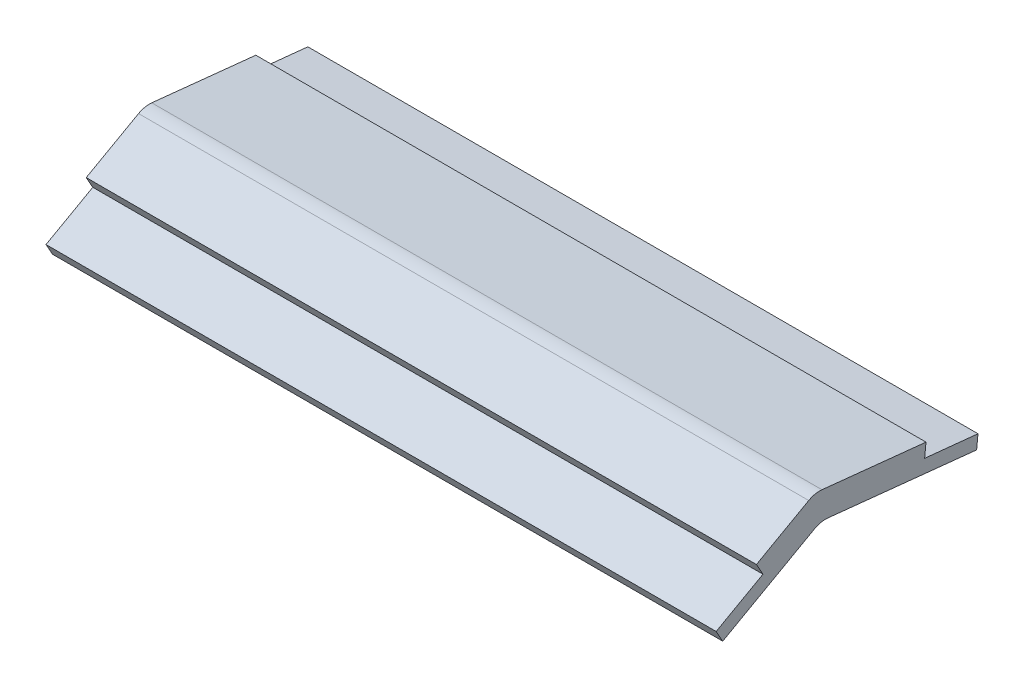
SolidWorks part; units mm, degrees
ref_plane "Front Plane" through (0, 0, 0) normal (0, 0, 1) x (1, 0, 0)
ref_plane "Top Plane" through (0, 0, 0) normal (0, 1, 0) x (1, 0, 0)
ref_plane "Right Plane" through (0, 0, 0) normal (1, 0, 0) x (0, 0, -1)
sketch "Sketch1" plane through (0, 0, 0) normal (1, 0, 0) x (0, 0, -1)
  line L6 (-17.0451, 11.0948) -> (-15.5805, 8.4766)
  line L7 (-17.0451, 11.0948) -> (-5.3363, 17.6448)
  line L8 (-2.3791, 18.2544) -> (20.9122, 15.8371)
  line L9 (20.9122, 15.8371) -> (20.6102, 12.8523)
  line L12 (-3.9542, 18.4179) -> (0, 0) construction
  line L13 (-15.5805, 8.4766) -> (-26.0533, 2.6182)
  line L14 (-26.0533, 2.6182) -> (-24.5887, 0)
  line L15 (-24.5887, 0) -> (-4.0185, 11.5069)
  line L16 (-1.0613, 12.1166) -> (32.2396, 8.6604)
  line L18 (20.6102, 12.8523) -> (32.5493, 11.6444)
  line L19 (32.5493, 11.6444) -> (32.2396, 8.6604)
  line L20 (0, 0) -> (50000, 0) construction
  arc A0 (-2.3791, 18.2544) -> (-5.3363, 17.6448) centre (-2.8952, 13.2811) ccw
  arc A1 (-1.0613, 12.1166) -> (-4.0185, 11.5069) centre (-1.5775, 7.1433) ccw
  point P23 (-2.6365, 12.2801)
  dimension "D12" = 5
  dimension "D13" = 5
  dimension "D1" = 25
  dimension "D2" = 15
  dimension "D3" = 145
  dimension "D5" = 12
  dimension "D6" = 12
  dimension "D7" = 3
  dimension "D8" = 3
  dimension "D9" = 3
  dimension "D10" = 3
extrude "Boss-Extrude1" add sketch "Sketch1" along normal blind 150
